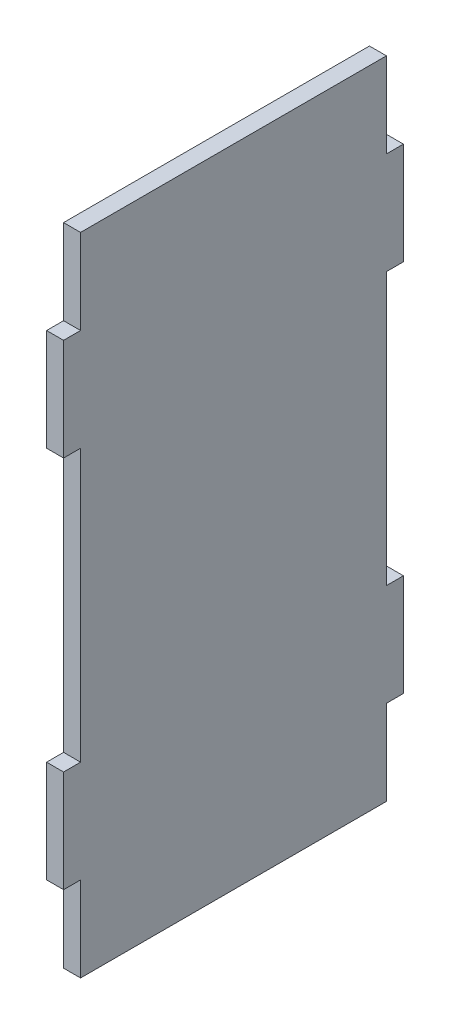
SolidWorks part; units mm, degrees
ref_plane "Front Plane" through (0, 0, 0) normal (0, 0, 1) x (1, 0, 0)
ref_plane "Top Plane" through (0, 0, 0) normal (0, 1, 0) x (1, 0, 0)
ref_plane "Right Plane" through (0, 0, 0) normal (1, 0, 0) x (0, 0, -1)
sketch "Sketch1" plane through (0, 0, 0) normal (1, 0, 0) x (0, 0, -1)
  line L0 (0, 60.325) -> (124.2325, 60.325) construction
  line L1 (0, 0) -> (57.15, 0)
  line L2 (0, 0) -> (0, 15.875)
  line L3 (0, 120.65) -> (57.15, 120.65)
  line L4 (57.15, 0) -> (57.15, 15.875)
  line L5 (0, 104.775) -> (-3.175, 104.775)
  line L6 (-3.175, 104.775) -> (-3.175, 85.725)
  line L7 (-3.175, 85.725) -> (0, 85.725)
  line L8 (-3.175, 34.925) -> (0, 34.925)
  line L9 (-3.175, 15.875) -> (-3.175, 34.925)
  line L10 (0, 15.875) -> (-3.175, 15.875)
  line L11 (28.575, 120.65) -> (28.575, -18.3674) construction
  line L12 (60.325, 15.875) -> (60.325, 34.925)
  line L13 (57.15, 15.875) -> (60.325, 15.875)
  line L14 (60.325, 34.925) -> (57.15, 34.925)
  line L15 (60.325, 85.725) -> (57.15, 85.725)
  line L16 (60.325, 104.775) -> (60.325, 85.725)
  line L17 (57.15, 104.775) -> (60.325, 104.775)
  line L18 (57.15, 104.775) -> (57.15, 120.65)
  line L19 (0, 104.775) -> (0, 120.65)
  line L20 (0, 34.925) -> (0, 85.725)
  line L21 (57.15, 34.925) -> (57.15, 85.725)
  dimension "D1" = 120.65
  dimension "D2" = 57.15
  dimension "D3" = 3.175
  dimension "D4" = 19.05
  dimension "D5" = 25.4
extrude "Boss-Extrude1" add sketch "Sketch1" along normal blind 3.175
